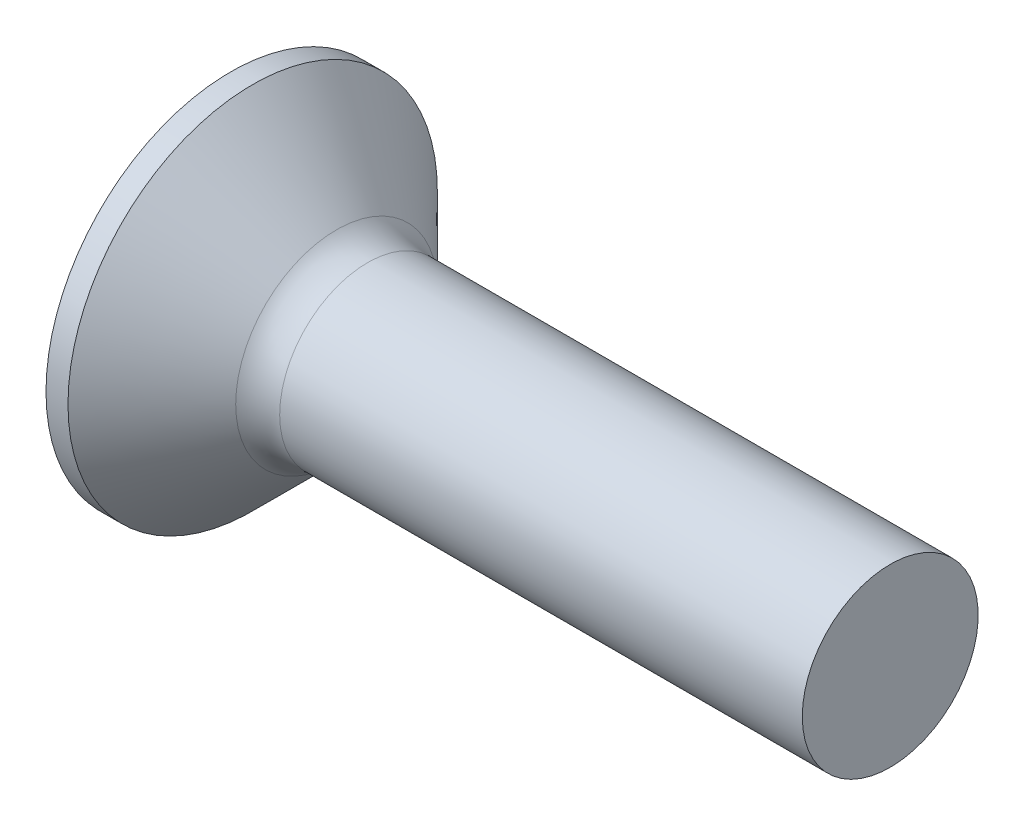
SolidWorks part; units mm, degrees
ref_plane "Plane1" through (0, 0, 0) normal (0, 0, 1) x (1, 0, 0)
ref_plane "Plane2" through (0, 0, 0) normal (0, 1, 0) x (1, 0, 0)
ref_plane "Plane3" through (0, 0, 0) normal (1, 0, 0) x (0, 0, -1)
sketch "BodySke" plane through (0, 0, 0) normal (0, 0, 1) x (1, 0, 0)
  line L0 (0, 0) -> (0, 4.2)
  line L1 (0, 4.2) -> (0.5, 4.2)
  line L2 (2.7, 2) -> (15, 2)
  line L3 (15, 2) -> (15, 0)
  line L4 (15, 0) -> (0, 0)
  line L5 (-6.35, 0) -> (82.55, 0) construction
  line L6 (2.7, -2) -> (15, -2) construction
  line L7 (0.5, -4.2) -> (2.7, -2) construction
  line L8 (0.5, 4.2) -> (2.7, 2)
  line L9 (0, -4.2) -> (0.5, -4.2) construction
  line L10 (3.4, 3.5875) -> (3.4, -5.9375) construction
  line L11 (-5, 6.35) -> (-5, -3.175) construction
  dimension "Diameter" = 4
  dimension "Length" = 15
  dimension "Head_ht" = 2.7
  dimension "Head_dia" = 8.4
  dimension "Head_ang" = 90
  dimension "D6" = 0.5
  dimension "Advance" = 0.7
  dimension "Thread_nom" = 20
revolve "Base-Revolve" add sketch "BodySke"
cosmetic thread "ThreadCosmetic"
fillet "Fillet1" radius 1 1 edges at (2.7, 0, 2)
sketch "Sketch3" plane through (0, 0, 0) normal (-1, 0, 0) x (0, 0, 1)
  line L0 (-0.515, 2.2) -> (0.515, 2.2)
  line L1 (0.515, 2.2) -> (0.515, -2.2)
  line L2 (0.515, -2.2) -> (-0.515, -2.2)
  line L3 (-0.515, -2.2) -> (-0.515, 2.2)
  dimension "D1" = 2.2
  dimension "Cross_dia" = 4.4
  dimension "D2" = 0.515
  dimension "Cross_width" = 1.03
ref_plane "Plane4" through (2.51, 0, 0) normal (-1, 0, 0) x (0, 0, 1)
sketch "Sketch4" plane through (2.51, 0, 0) normal (-1, 0, 0) x (0, 0, 1)
  line L0 (-0.515, 0.9486) -> (0.515, 0.9486)
  line L3 (0.515, 0.9486) -> (0.515, -0.9486)
  line L4 (0.515, -0.9486) -> (-0.515, -0.9486)
  line L5 (-0.515, -0.9486) -> (-0.515, 0.9486)
  dimension "D1" = 1.03
  dimension "D2" = 1.8971
  dimension "D3" = 0.515
  dimension "D4" = 0.9486
loft "Recess" cut profiles "Sketch3", "Sketch4"
pattern_circular "RecPat" count 2 every 90 about axis through (0, 0, 0) along (1, 0, 0) of "Recess"
sketch "RecCorSke" plane through (0, 0, 0) normal (0, 0, 1) x (1, 0, 0)
  line L0 (-3.175, 0) -> (15.875, 0) construction
  line L2 (0, 0) -> (0, 1.0265)
  line L3 (0, 1.0265) -> (2.51, 0.851)
  line L4 (2.51, 0.851) -> (2.7865, 0)
  line L5 (2.7865, 0) -> (0, 0)
  dimension "Diameter" = 1.702
  dimension "Depth" = 2.51
  dimension "Draft_angle" = 4
  dimension "Bottom_angle" = 18
revolve "RecessCore" cut sketch "RecCorSke" angle 360 about L0
sketch "ThdSchSke" plane through (0, 0, 0) normal (0, 0, 1) x (1, 0, 0)
  line L0 (3.4, -1.61) -> (3.1269, -2)
  line L1 (3.4, -1.61) -> (3.6731, -2)
  line L2 (3.6731, -2) -> (3.6731, -2.5)
  line L3 (-3.175, 0) -> (5.1513, 0) construction
  line L5 (3.6731, -2.5) -> (3.1269, -2.5)
  line L6 (3.1269, -2.5) -> (3.1269, -2)
  line L7 (0, 4.2) -> (0, -4.2) construction
  dimension "Thread_minor" = 3.22
  dimension "Diameter" = 4
  dimension "Start" = 3.4
  dimension "SideAngle" = 55
  dimension "VeeAngle" = 70
  dimension "Overcut" = 5
revolve "ThreadSchematic" [suppressed] cut sketch "ThdSchSke" angle 360 about L3
pattern_linear "ThdSchPat" [suppressed]
equation "\"D1@Sketch3\" = \"Cross_dia@Sketch3\" / 2"
equation "\"D2@Sketch3\" = \"Cross_width@Sketch3\" / 2"
equation "\"Depth@RecCorSke\" = \"Cross_depth@Plane4\""
equation "\"D1@Sketch4\" = \"Cross_width@Sketch3\""
equation "\"D2@Sketch4\" = \"Cross_dia@Sketch3\" - 2.0 * \"Cross_depth@Plane4\" * tan(26.5  * 0.017453292)"
equation "\"D3@Sketch4\" = \"D1@Sketch4\" / 2"
equation "\"D4@Sketch4\" = \"D2@Sketch4\" / 2"
equation "\"Thread_length@ThreadCosmetic\" = ((sgn( (\"Length@BodySke\" - \"Advance@BodySke\" * 1.0 - \"Head_ht@BodySke\" ) - \"Thread_nom@BodySke\" )-1)*( (\"Length@BodySke\" - \"Advance@BodySke\" * 1.0 - \"Head_ht@BodySke\" ) - \"Thread_nom@BodySke\" ))/-2+ \"Thread_nom@BodySke\""
equation "\"Thread_minor@ThdSchSke\" = \"Thread_minor@ThreadCosmetic\""
equation "\"Diameter@ThdSchSke\" = \"Diameter@BodySke\""
equation "\"Overcut@ThdSchSke\" = \"Diameter@BodySke\" * 1.25"
equation "\"Start@ThdSchSke\" = 0.000001 + \"Length@BodySke\" - \"Thread_length@ThreadCosmetic\"  '---Countersunk---"
equation "\"Num_threads@ThdSchPat\" = int( \"Thread_length@ThreadCosmetic\" / \"Advance@BodySke\" + 0.999 )  + 1"
equation "\"Advance@ThdSchPat\" = \"Thread_length@ThreadCosmetic\" /  (\"Num_threads@ThdSchPat\" - 1) 'relax it"
